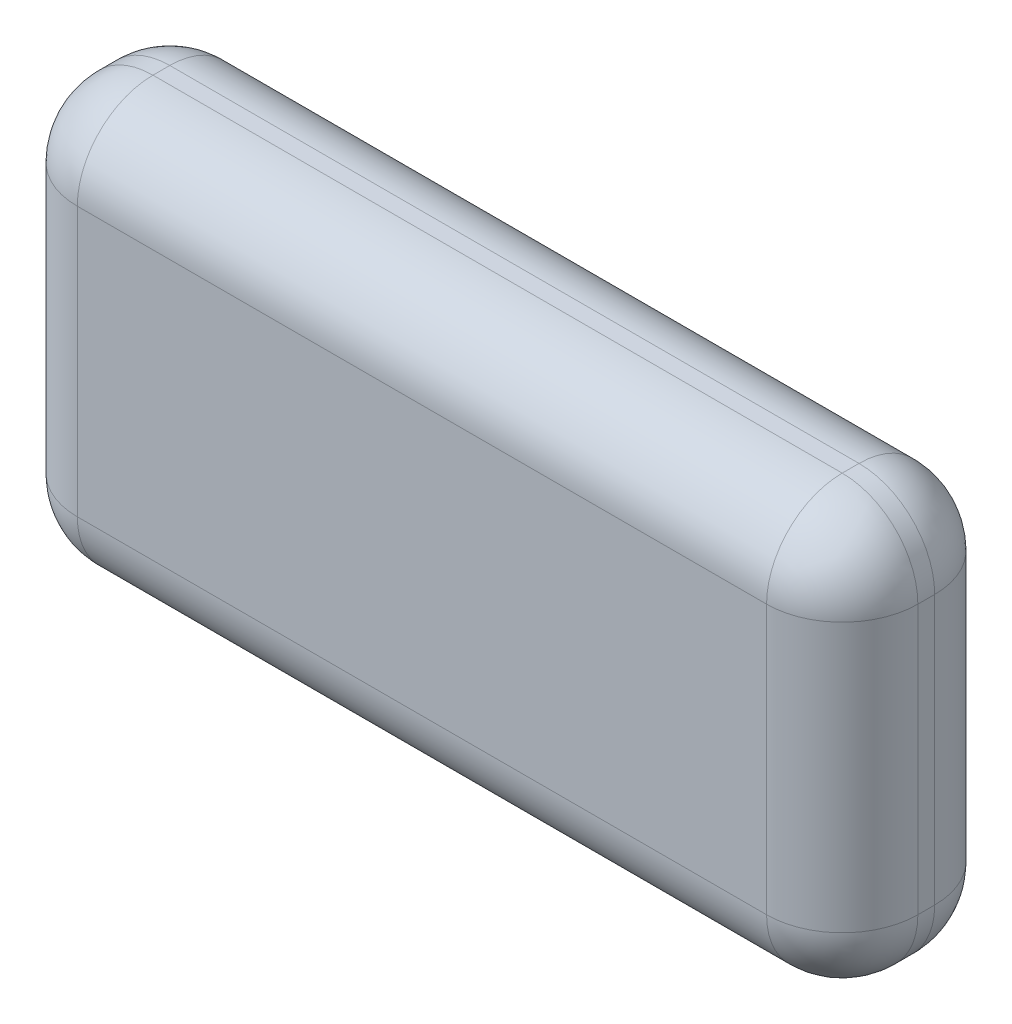
SolidWorks part; units mm, degrees
ref_plane "Front Plane" through (0, 0, 0) normal (0, 0, 1) x (1, 0, 0)
ref_plane "Top Plane" through (0, 0, 0) normal (0, 1, 0) x (1, 0, 0)
ref_plane "Right Plane" through (0, 0, 0) normal (1, 0, 0) x (0, 0, -1)
sketch "Sketch1" plane through (0, 0, 0) normal (0, 0, 1) x (1, 0, 0)
  line L1 (-21.4107, 234.8939) -> (478.5893, 234.8939)
  line L2 (-21.4107, 234.8939) -> (-21.4107, -15.1061)
  line L3 (-21.4107, -15.1061) -> (478.5893, -15.1061)
  line L4 (478.5893, 234.8939) -> (478.5893, -15.1061)
  dimension "D1" = 500
  dimension "D2" = 250
extrude "Boss-Extrude1" add sketch "Sketch1" along normal blind 100
fillet "Fillet1" radius 45 12 edges at (228.5893, 234.8939, 100) (478.5893, 109.8939, 100) (228.5893, -15.1061, 100) (-21.4107, 109.8939, 100) (228.5893, -15.1061, 0) (478.5893, 109.8939, 0) (228.5893, 234.8939, 0) (-21.4107, 109.8939, 0) (-21.4107, -15.1061, 50) (-21.4107, 234.8939, 50) (478.5893, 234.8939, 50) (478.5893, -15.1061, 50)
